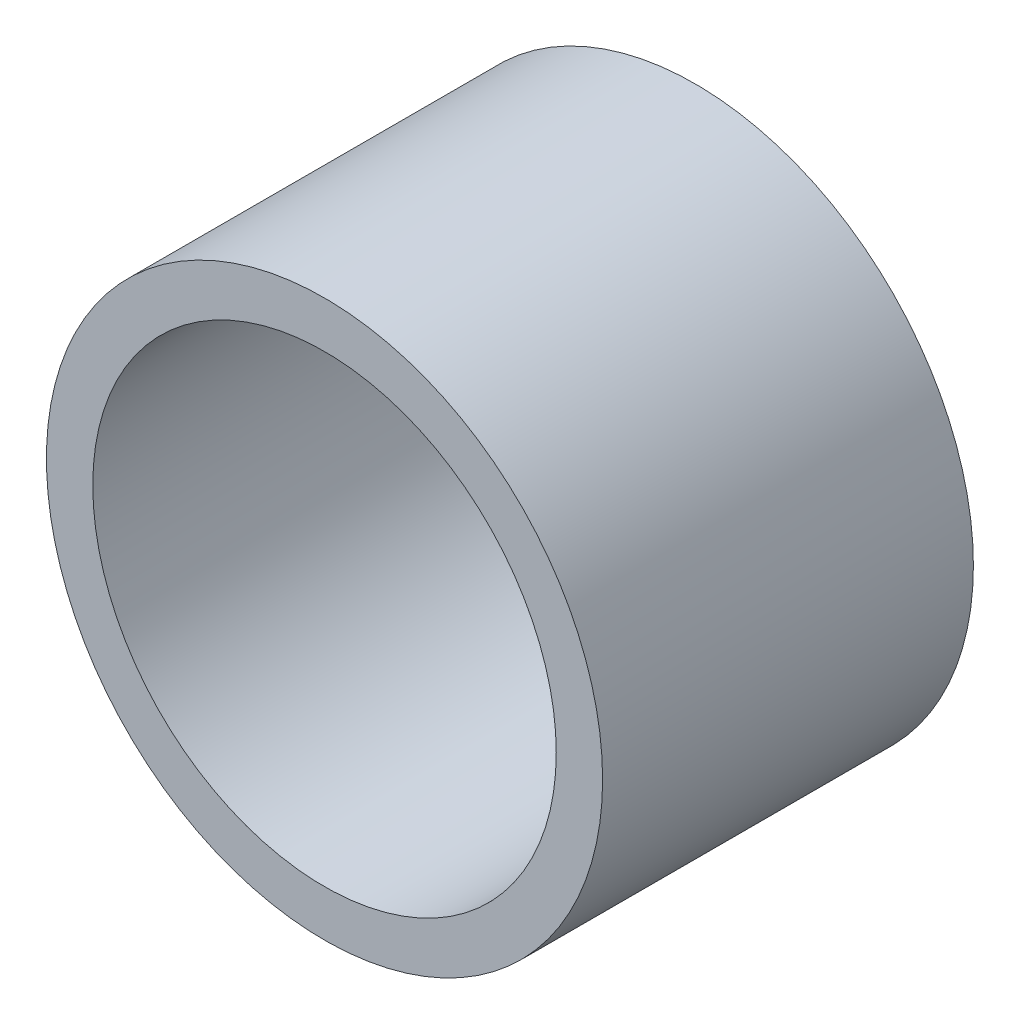
SolidWorks part; units mm, degrees
ref_plane "前视基准面" through (0, 0, 0) normal (0, 0, 1) x (1, 0, 0)
ref_plane "上视基准面" through (0, 0, 0) normal (0, 1, 0) x (1, 0, 0)
ref_plane "右视基准面" through (0, 0, 0) normal (1, 0, 0) x (0, 0, -1)
sketch "草图1" plane through (0, 0, 0) normal (0, 0, 1) x (1, 0, 0)
  circle A0 centre (0, 0) radius 6
  circle A1 centre (0, 0) radius 5
  dimension "D1" = 10
  dimension "D2" = 12
extrude "凸台-拉伸1" add sketch "草图1" along normal blind 8
